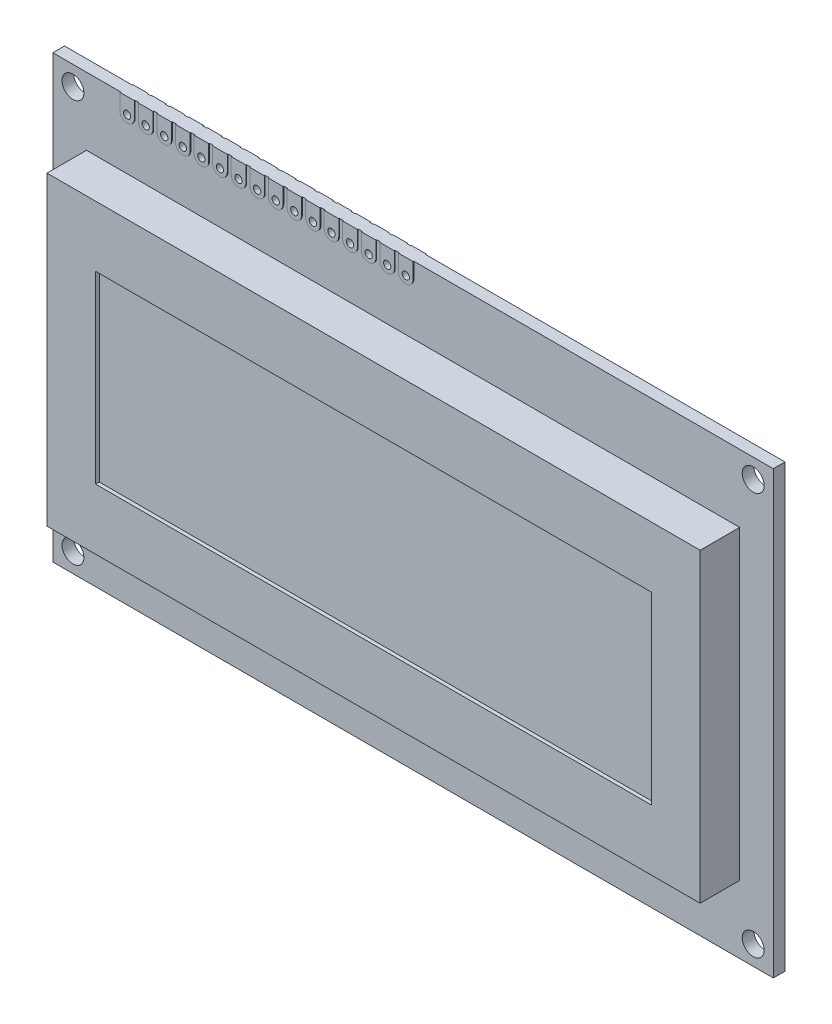
SolidWorks part; units mm, degrees
ref_plane "Front Plane" through (0, 0, 0) normal (0, 0, 1) x (1, 0, 0)
ref_plane "Top Plane" through (0, 0, 0) normal (0, 1, 0) x (1, 0, 0)
ref_plane "Right Plane" through (0, 0, 0) normal (1, 0, 0) x (0, 0, -1)
sketch "Sketch1" plane through (0, 0, 0) normal (0, 0, 1) x (1, 0, 0)
  line L1 (0, 0) -> (98.5, 0)
  line L2 (0, 0) -> (0, 60.3)
  line L3 (0, 60.3) -> (98.5, 60.3)
  line L4 (98.5, 0) -> (98.5, 60.3)
  dimension "D1" = 60.3
  dimension "D2" = 98.5
extrude "Boss-Extrude1" add sketch "Sketch1" against normal blind 1.6
sketch "Sketch2" plane through (0, 0, 0) normal (0, 0, 1) x (1, 0, 0)
  line L1 (2.75, 57.65) -> (95.75, 57.65) construction
  line L2 (2.75, 57.65) -> (2.75, 2.65) construction
  line L3 (2.75, 2.65) -> (95.75, 2.65) construction
  line L4 (95.75, 57.65) -> (95.75, 2.65) construction
  line L6 (0, 0) -> (98.5, 0) construction
  line L7 (0, 60.3) -> (0, 0) construction
  point P4 (49.25, 2.65)
  point P7 (49.25, 0)
  point P8 (2.75, 30.15)
  point P11 (0, 30.15)
  dimension "D3" = 93
  dimension "D4" = 55
hole_wizard "Ø3.0 (3) Diameter Hole1" positions "Sketch3" profile "Sketch4" hole size "Ø3.0" standard "ANSI Metric" end condition through all
sketch "Sketch3" plane through (0, 0, 0) normal (0, 0, 1) x (1, 0, 0)
  point P0 (2.75, 57.65)
  point P3 (95.75, 57.65)
  point P6 (95.75, 2.65)
  point P9 (2.75, 2.65)
sketch "Sketch4" plane through (2.75, 57.65, 0) normal (1, 0, 0) x (0, -1, 0)
  line L0 (0, 0) -> (0, 1.6)
  line L1 (0, 1.6) -> (1.5, 1.6)
  line L2 (1.5, 1.6) -> (1.5, 0)
  line L5 (1.5, 0) -> (0, 0)
  line L11 (0, -6.35) -> (0, 107.95) construction
  dimension "Thru Hole Dia." = 3
  dimension "Thru Hole Depth" = 1.6
sketch "Sketch5" plane through (0, 0, 0) normal (0, 0, 1) x (1, 0, 0)
  line L0 (98.5, 60.3) -> (0, 60.3) construction
  line L1 (4.6, 51.05) -> (93.9, 51.05)
  line L2 (4.6, 51.05) -> (4.6, 9.25)
  line L3 (4.6, 9.25) -> (93.9, 9.25)
  line L4 (93.9, 51.05) -> (93.9, 9.25)
  line L5 (0, 60.3) -> (0, 0) construction
  line L6 (0, 0) -> (98.5, 0) construction
  point P4 (49.25, 51.05)
  point P7 (49.25, 60.3)
  point P8 (4.6, 30.15)
  point P11 (0, 30.15)
  dimension "D1" = 41.8
  dimension "D2" = 9.25
  dimension "D3" = 89.3
  dimension "D4" = 4.6
extrude "Boss-Extrude2" add sketch "Sketch5" along normal blind 5.4
sketch "Sketch6" plane through (0, 0, 5.4) normal (0, 0, 1) x (1, 0, 0)
  line L0 (4.6, 51.05) -> (4.6, 9.25) construction
  line L1 (11.25, 42.75) -> (87.25, 42.75)
  line L2 (11.25, 42.75) -> (11.25, 17.55)
  line L3 (11.25, 17.55) -> (87.25, 17.55)
  line L4 (87.25, 42.75) -> (87.25, 17.55)
  line L5 (93.9, 51.05) -> (4.6, 51.05) construction
  point P4 (11.25, 30.15)
  point P7 (4.6, 30.15)
  point P8 (49.25, 42.75)
  point P11 (49.25, 51.05)
  dimension "D1" = 76
  dimension "D2" = 25.2
extrude "Cut-Extrude1" cut sketch "Sketch6" against normal blind 0.5
sketch "Sketch7" plane through (0, 0, -1.6) normal (0, 0, -1) x (-1, 0, 0)
  line L0 (-98.5, 60.3) -> (0, 60.3) construction
  line L2 (-11.25, 58.15) -> (-11.25, 60.3)
  line L3 (-11.25, 60.3) -> (-9.25, 60.3)
  line L4 (-9.25, 58.15) -> (-9.25, 60.3)
  line L5 (0, 60.3) -> (0, 0) construction
  line L6 (-11.79, 58.15) -> (-11.79, 60.3)
  line L7 (-13.79, 58.15) -> (-13.79, 60.3)
  line L8 (-13.79, 60.3) -> (-11.79, 60.3)
  line L9 (-14.33, 58.15) -> (-14.33, 60.3)
  line L10 (-16.33, 58.15) -> (-16.33, 60.3)
  line L11 (-16.33, 60.3) -> (-14.33, 60.3)
  line L12 (-16.87, 58.15) -> (-16.87, 60.3)
  line L13 (-18.87, 58.15) -> (-18.87, 60.3)
  line L14 (-18.87, 60.3) -> (-16.87, 60.3)
  line L15 (-19.41, 58.15) -> (-19.41, 60.3)
  line L16 (-21.41, 58.15) -> (-21.41, 60.3)
  line L17 (-21.41, 60.3) -> (-19.41, 60.3)
  line L18 (-21.95, 58.15) -> (-21.95, 60.3)
  line L19 (-23.95, 58.15) -> (-23.95, 60.3)
  line L20 (-23.95, 60.3) -> (-21.95, 60.3)
  line L21 (-24.49, 58.15) -> (-24.49, 60.3)
  line L22 (-26.49, 58.15) -> (-26.49, 60.3)
  line L23 (-26.49, 60.3) -> (-24.49, 60.3)
  line L24 (-27.03, 58.15) -> (-27.03, 60.3)
  line L25 (-29.03, 58.15) -> (-29.03, 60.3)
  line L26 (-29.03, 60.3) -> (-27.03, 60.3)
  line L27 (-29.57, 58.15) -> (-29.57, 60.3)
  line L28 (-31.57, 58.15) -> (-31.57, 60.3)
  line L29 (-31.57, 60.3) -> (-29.57, 60.3)
  line L30 (-32.11, 58.15) -> (-32.11, 60.3)
  line L31 (-34.11, 58.15) -> (-34.11, 60.3)
  line L32 (-34.11, 60.3) -> (-32.11, 60.3)
  line L33 (-34.65, 58.15) -> (-34.65, 60.3)
  line L34 (-36.65, 58.15) -> (-36.65, 60.3)
  line L35 (-36.65, 60.3) -> (-34.65, 60.3)
  line L36 (-37.19, 58.15) -> (-37.19, 60.3)
  line L37 (-39.19, 58.15) -> (-39.19, 60.3)
  line L38 (-39.19, 60.3) -> (-37.19, 60.3)
  line L39 (-39.73, 58.15) -> (-39.73, 60.3)
  line L40 (-41.73, 58.15) -> (-41.73, 60.3)
  line L41 (-41.73, 60.3) -> (-39.73, 60.3)
  line L42 (-42.27, 58.15) -> (-42.27, 60.3)
  line L43 (-44.27, 58.15) -> (-44.27, 60.3)
  line L44 (-44.27, 60.3) -> (-42.27, 60.3)
  line L45 (-44.81, 58.15) -> (-44.81, 60.3)
  line L46 (-46.81, 58.15) -> (-46.81, 60.3)
  line L47 (-46.81, 60.3) -> (-44.81, 60.3)
  line L48 (-47.35, 58.15) -> (-47.35, 60.3)
  line L49 (-49.35, 58.15) -> (-49.35, 60.3)
  line L50 (-49.35, 60.3) -> (-47.35, 60.3)
  circle A0 centre (-10.25, 58.15) radius 1 construction
  arc A1 (-11.25, 58.15) -> (-9.25, 58.15) centre (-10.25, 58.15) ccw
  arc A2 (-13.79, 58.15) -> (-11.79, 58.15) centre (-12.79, 58.15) ccw
  circle A3 centre (-12.79, 58.15) radius 1 construction
  arc A4 (-16.33, 58.15) -> (-14.33, 58.15) centre (-15.33, 58.15) ccw
  circle A5 centre (-15.33, 58.15) radius 1 construction
  arc A6 (-18.87, 58.15) -> (-16.87, 58.15) centre (-17.87, 58.15) ccw
  circle A7 centre (-17.87, 58.15) radius 1 construction
  arc A8 (-21.41, 58.15) -> (-19.41, 58.15) centre (-20.41, 58.15) ccw
  circle A9 centre (-20.41, 58.15) radius 1 construction
  arc A10 (-23.95, 58.15) -> (-21.95, 58.15) centre (-22.95, 58.15) ccw
  circle A11 centre (-22.95, 58.15) radius 1 construction
  arc A12 (-26.49, 58.15) -> (-24.49, 58.15) centre (-25.49, 58.15) ccw
  circle A13 centre (-25.49, 58.15) radius 1 construction
  arc A14 (-29.03, 58.15) -> (-27.03, 58.15) centre (-28.03, 58.15) ccw
  circle A15 centre (-28.03, 58.15) radius 1 construction
  arc A16 (-31.57, 58.15) -> (-29.57, 58.15) centre (-30.57, 58.15) ccw
  circle A17 centre (-30.57, 58.15) radius 1 construction
  arc A18 (-34.11, 58.15) -> (-32.11, 58.15) centre (-33.11, 58.15) ccw
  circle A19 centre (-33.11, 58.15) radius 1 construction
  arc A20 (-36.65, 58.15) -> (-34.65, 58.15) centre (-35.65, 58.15) ccw
  circle A21 centre (-35.65, 58.15) radius 1 construction
  arc A22 (-39.19, 58.15) -> (-37.19, 58.15) centre (-38.19, 58.15) ccw
  circle A23 centre (-38.19, 58.15) radius 1 construction
  arc A24 (-41.73, 58.15) -> (-39.73, 58.15) centre (-40.73, 58.15) ccw
  circle A25 centre (-40.73, 58.15) radius 1 construction
  arc A26 (-44.27, 58.15) -> (-42.27, 58.15) centre (-43.27, 58.15) ccw
  circle A27 centre (-43.27, 58.15) radius 1 construction
  arc A28 (-46.81, 58.15) -> (-44.81, 58.15) centre (-45.81, 58.15) ccw
  circle A29 centre (-45.81, 58.15) radius 1 construction
  arc A30 (-49.35, 58.15) -> (-47.35, 58.15) centre (-48.35, 58.15) ccw
  circle A31 centre (-48.35, 58.15) radius 1 construction
  dimension "D3" = 2
  dimension "D1" = 2.15
  dimension "D2" = 10.25
  dimension "D4" = 16
extrude "Boss-Extrude3" add sketch "Sketch7" along normal blind 0.1 and the other way blind 1.7
hole_wizard "Ø1.0 (1) Diameter Hole1" positions "Sketch8" profile "Sketch9" hole size "Ø1.0" standard "ANSI Metric" end condition through all
sketch "Sketch8" plane through (0, 0, 0.1) normal (0, 0, 1) x (1, 0, 0)
  point P0 (10.25, 58.15)
  point P3 (12.79, 58.15)
  point P6 (15.33, 58.15)
  point P9 (17.87, 58.15)
  point P12 (20.41, 58.15)
  point P15 (22.95, 58.15)
  point P18 (25.49, 58.15)
  point P21 (28.03, 58.15)
  point P24 (30.57, 58.15)
  point P27 (33.11, 58.15)
  point P30 (35.65, 58.15)
  point P33 (38.19, 58.15)
  point P36 (40.73, 58.15)
  point P39 (43.27, 58.15)
  point P42 (45.81, 58.15)
  point P45 (48.35, 58.15)
sketch "Sketch9" plane through (10.25, 58.15, 0.1) normal (1, 0, 0) x (0, -1, 0)
  line L0 (0, 0) -> (0, 1.8)
  line L1 (0, 1.8) -> (0.5, 1.8)
  line L2 (0.5, 1.8) -> (0.5, 0)
  line L5 (0.5, 0) -> (0, 0)
  line L11 (0, -6.35) -> (0, 107.95) construction
  dimension "Thru Hole Dia." = 1
  dimension "Thru Hole Depth" = 1.8
